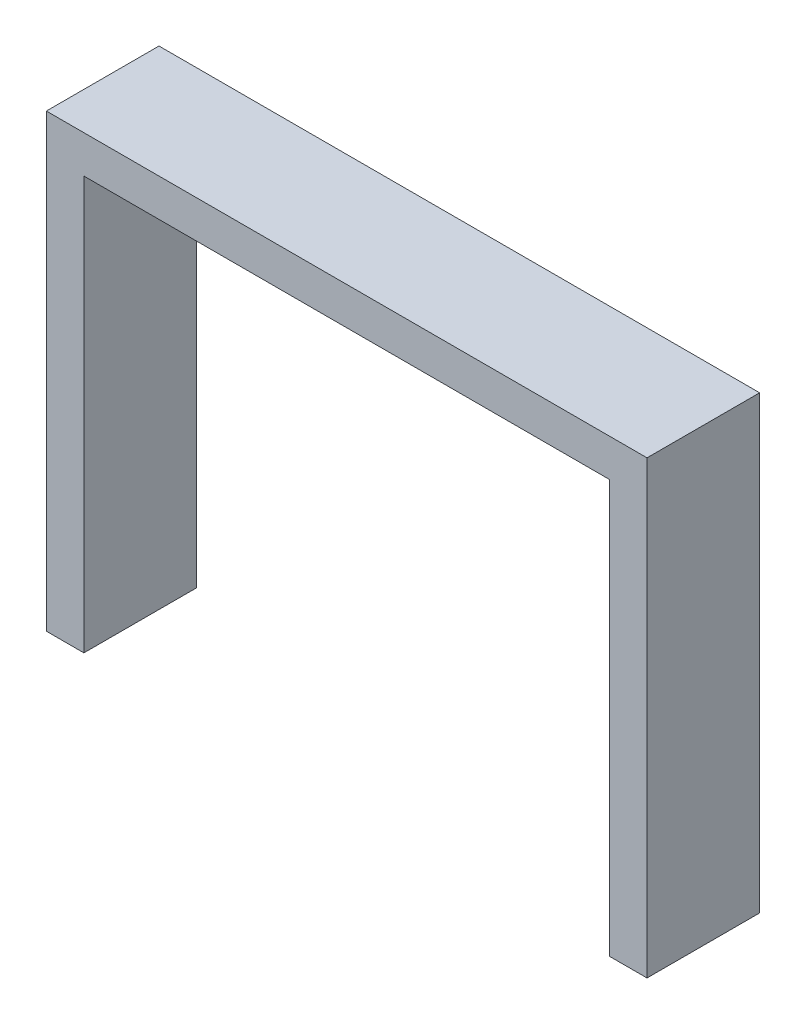
SolidWorks part; units mm, degrees
ref_plane "Front Plane" through (0, 0, 0) normal (1, 0, 0) x (0, 1, 0)
ref_plane "Top Plane" through (0, 0, 0) normal (0, 0, 1) x (0, 1, 0)
ref_plane "Right Plane" through (0, 0, 0) normal (0, 1, 0) x (-1, 0, 0)
sketch "Sketch2" plane through (0, 0, 0) normal (0, 0, 1) x (0, 1, 0)
  line L0 (-30, -35) -> (-30, -40)
  line L1 (-30, 40) -> (30, 40)
  line L2 (-30, 40) -> (-30, 35)
  line L3 (-30, -40) -> (30, -40)
  line L4 (30, 40) -> (30, -40)
  line L5 (-30, 40) -> (30, -40) construction
  line L6 (-30, -40) -> (30, 40) construction
  line L7 (25, 35) -> (-30, 35)
  line L8 (25, 35) -> (25, -35)
  line L9 (25, -35) -> (-30, -35)
  point P0 (0, 0)
  dimension "D1" = 80
  dimension "D2" = 60
  dimension "D3" = 5
  dimension "D4" = 5
  dimension "D5" = 5
extrude "Boss-Extrude1" add sketch "Sketch2" against normal blind 15
scale "Scale1" scale about centroid uniform scaling yes scale factor 0.7
